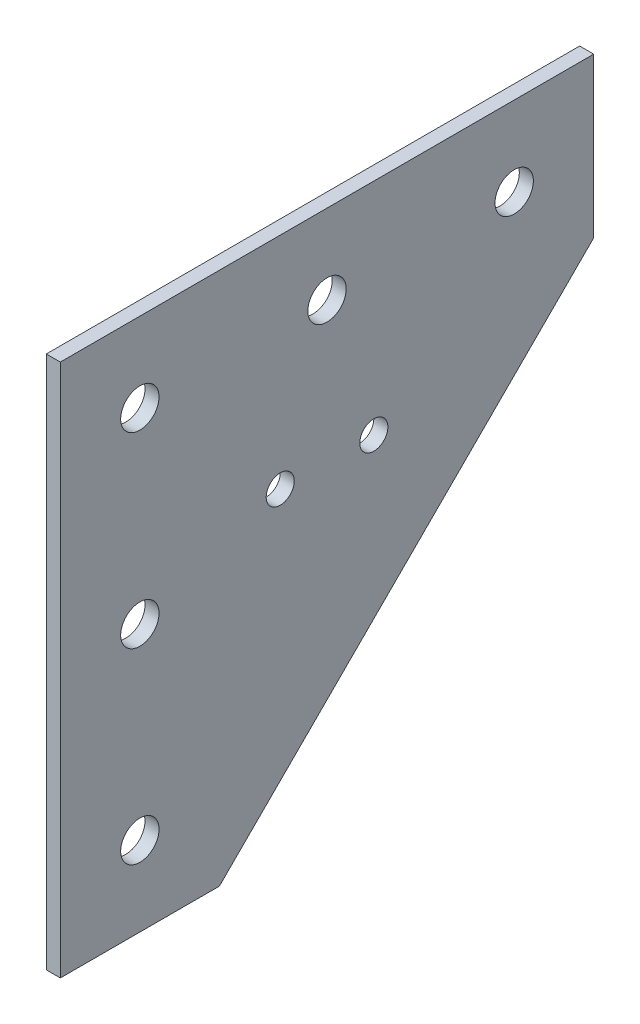
SolidWorks part; units mm, degrees
material "Простая углеродистая сталь"
ref_plane "Спереди" through (0, 0, 0) normal (0, 0, 1) x (1, 0, 0)
ref_plane "Сверху" through (0, 0, 0) normal (0, 1, 0) x (1, 0, 0)
ref_plane "Справа" through (0, 0, 0) normal (1, 0, 0) x (0, 0, -1)
sketch "Эскиз1" plane through (0, 0, 0) normal (1, 0, 0) x (0, 0, -1)
  line L1 (-57, 57) -> (57, 57)
  line L2 (-57, 57) -> (-57, -57)
  line L3 (-57, -57) -> (57, -57)
  line L4 (57, 57) -> (57, -57)
  line L5 (-57, 57) -> (57, -57) construction
  line L6 (-57, -57) -> (57, 57) construction
  point P0 (0, 0)
  dimension "D1" = 114
extrude "База" add sketch "Эскиз1" along normal blind 3
sketch "Эскиз2" plane through (3, 0, 0) normal (1, 0, 0) x (0, 0, -1)
  line L0 (40, 40) -> (0, 40) construction
  line L1 (0, 40) -> (-40, 40) construction
  line L2 (-40, 40) -> (-40, 0) construction
  line L3 (-40, 0) -> (-40, -40) construction
  line L4 (-57, 57) -> (-57, -57) construction
  line L5 (57, 57) -> (-57, 57) construction
  circle A1 centre (0, 40) radius 4.1
  circle A2 centre (40, 40) radius 4.1
  circle A3 centre (-40, 0) radius 4.1
  circle A4 centre (-40, -40) radius 4.1
  circle A5 centre (-40, 40) radius 4.1
  dimension "D1" = 8.2
  dimension "D3" = 17
  dimension "D4" = 17
  dimension "D5" = 40
extrude "Вырез-Вытянуть1" cut sketch "Эскиз2" against normal through all
sketch "Эскиз3" plane through (3, 0, 0) normal (1, 0, 0) x (0, 0, -1)
  line L0 (57, 23) -> (57, -57)
  line L1 (57, -57) -> (57, 57) construction
  line L2 (57, -57) -> (-23, -57)
  line L3 (-57, -57) -> (57, -57) construction
  line L4 (-23, -57) -> (57, 23)
  dimension "D1" = 34
extrude "Вырез-Вытянуть2" cut sketch "Эскиз3" against normal through all
sketch "Эскиз4" plane through (3, 0, 0) normal (1, 0, 0) x (0, 0, -1)
  line L0 (-57, 57) -> (-57, -57) construction
  line L1 (57, 57) -> (-57, 57) construction
  circle A0 centre (-10, 10) radius 3
  circle A1 centre (10, 10) radius 3
  dimension "D1" = 6
  dimension "D2" = 20
  dimension "D3" = 47
  dimension "D4" = 47
extrude "Вырез-Вытянуть3" cut sketch "Эскиз4" against normal through all
